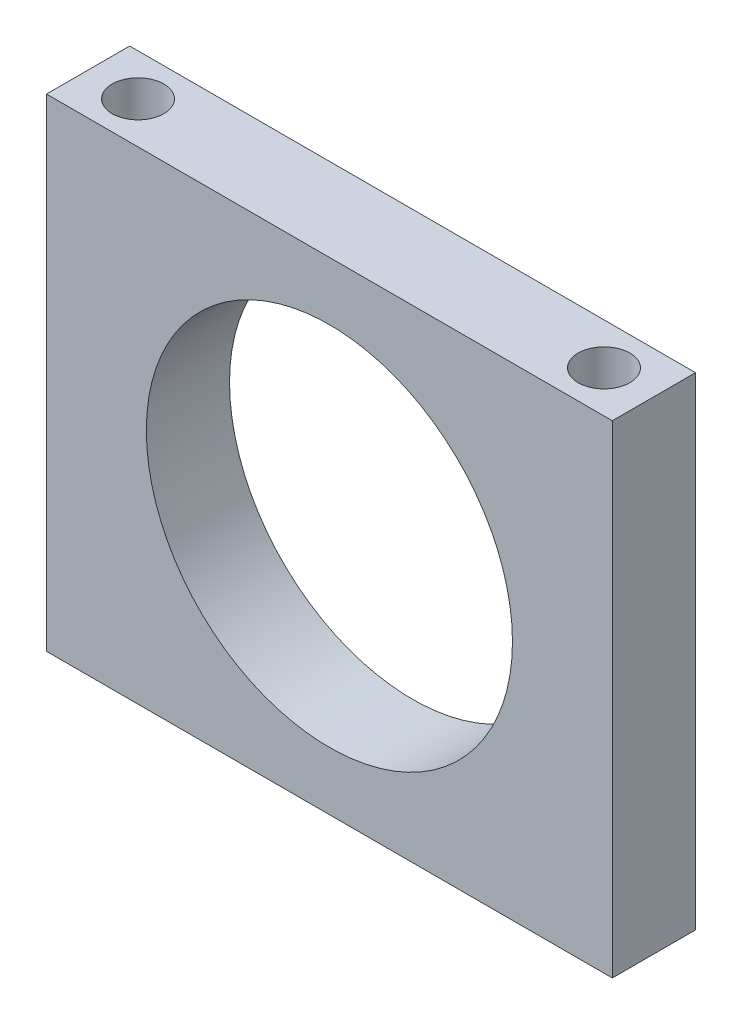
SolidWorks part; units mm, degrees
material "6061 合金"
ref_plane "前视基准面" through (0, 0, 0) normal (0, 0, 1) x (1, 0, 0)
ref_plane "上视基准面" through (0, 0, 0) normal (0, 1, 0) x (1, 0, 0)
ref_plane "右视基准面" through (0, 0, 0) normal (1, 0, 0) x (0, 0, -1)
sketch "草图1" plane through (0, 0, 0) normal (0, 0, 1) x (1, 0, 0)
  line L1 (17, 14.5) -> (-17, 14.5)
  line L2 (17, 14.5) -> (17, -14.5)
  line L3 (17, -14.5) -> (-17, -14.5)
  line L4 (-17, 14.5) -> (-17, -14.5)
  line L5 (17, 14.5) -> (-17, -14.5) construction
  line L6 (17, -14.5) -> (-17, 14.5) construction
  circle A0 centre (0, 0) radius 11
  dimension "D3" = 22
  dimension "D1" = 34
  dimension "D2" = 29
extrude "凸台-拉伸1" add sketch "草图1" along normal blind 5
sketch "草图2" plane through (0, 14.5, 0) normal (0, 1, 0) x (1, 0, 0)
  line L0 (-17, -2.5) -> (17, -2.5) construction
  line L1 (-17, -5) -> (-17, 0) construction
  line L2 (17, -5) -> (17, 0) construction
  line L3 (0, 0) -> (0, -5) construction
  line L4 (17, -5) -> (-17, -5) construction
  point P6 (-14, -2.5)
  point P12 (0, 0)
  point P13 (14, -2.5)
  dimension "D1" = 28
hole_wizard "孔1" positions "草图3" profile "草图4" legacy end condition through all
sketch "草图3" plane through (0, 14.5, 0) normal (0, 1, 0) x (1, 0, 0)
  point P0 (-14, -2.5)
  point P3 (14, -2.5)
sketch "草图4" plane through (-14, 14.5, 2.5) normal (1, 0, 0) x (0, 0, 1)
  line L0 (0, 0) -> (0, 29)
  line L1 (0, 29) -> (1.55, 29)
  line L2 (1.55, 29) -> (1.55, 0)
  line L3 (1.55, 0) -> (0, 0)
  line L4 (0, 110) -> (0, -10) construction
  dimension "直径" = 3.1
  dimension "深度" = 29
